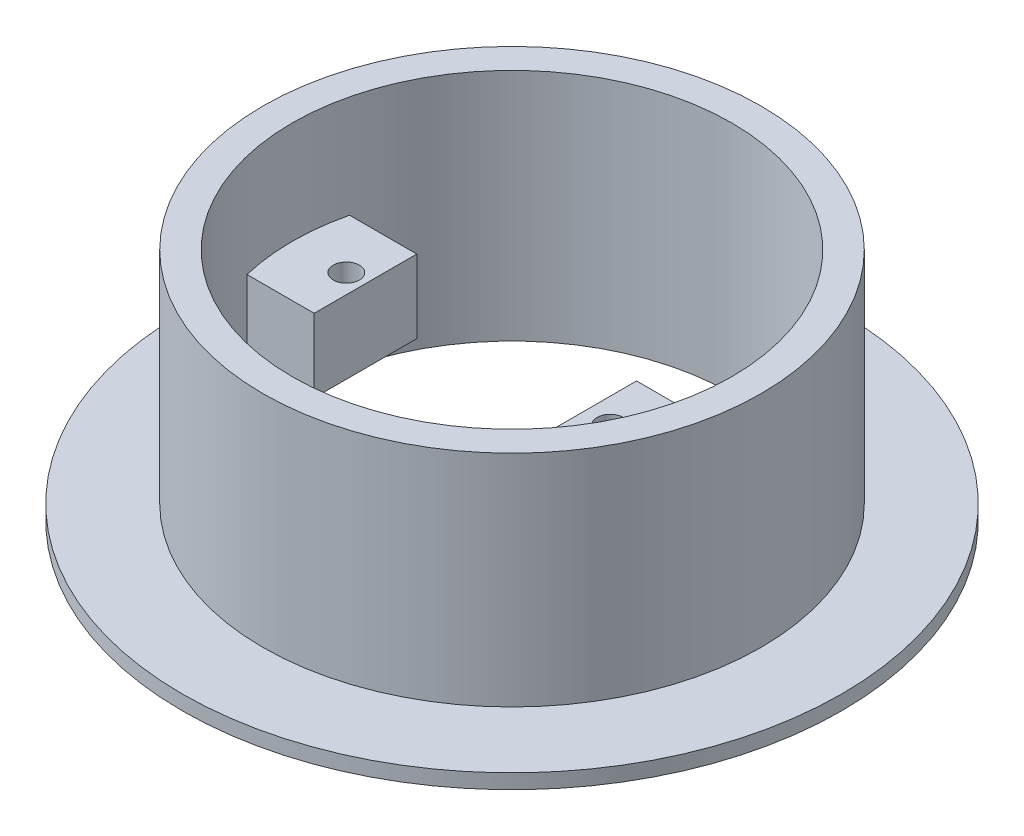
SolidWorks part; units mm, degrees
ref_plane "Front Plane" through (0, 0, 0) normal (0, 0, 1) x (1, 0, 0)
ref_plane "Top Plane" through (0, 0, 0) normal (0, 1, 0) x (1, 0, 0)
ref_plane "Right Plane" through (0, 0, 0) normal (1, 0, 0) x (0, 0, -1)
sketch "Sketch1" plane through (0, 0, 0) normal (0, 1, 0) x (1, 0, 0)
  circle A0 centre (0, 0) radius 45
  circle A1 centre (0, 0) radius 30
  dimension "D1" = 90
  dimension "D2" = 60
extrude "Boss-Extrude1" add sketch "Sketch1" along normal blind 2 contours A0
sketch "Sketch2" plane through (0, 2, 0) normal (0, 1, 0) x (1, 0, 0)
  circle A0 centre (0, 0) radius 30 construction
  circle A1 centre (0, 0) radius 30
  circle A2 centre (0, 0) radius 34
  dimension "D1" = 4
extrude "Boss-Extrude2" add sketch "Sketch2" along normal blind 30
ref_plane "Plane1" through (0, 12, 0) normal (0, 1, 0) x (1, 0, 0)
sketch "Sketch4" plane through (0, 0, 0) normal (0, 0, 1) x (1, 0, 0)
  line L0 (-45, 0) -> (45, 0) construction
  line L1 (10, 18) -> (17, 18)
  line L2 (10, 18) -> (10, 0)
  line L3 (10, 0) -> (17, 0)
  line L4 (17, 18) -> (17, 0)
  line L5 (34, 32) -> (-34, 32) construction
  line L6 (-30, 32) -> (-30, 2)
  line L7 (-20, 18) -> (-47, 18)
  line L8 (-20, 18) -> (-20, 8)
  line L9 (-20, 8) -> (-47, 8)
  line L10 (-47, 18) -> (-47, 8)
  line L11 (45, 2) -> (-45, 2) construction
  line L12 (-20, 8) -> (-30, -2)
  dimension "D1" = 10
  dimension "D2" = 7
  dimension "D3" = 14
  dimension "D4" = 30
  dimension "D5" = 27
  dimension "D6" = 10
  dimension "D7" = 45
  dimension "D8" = 14
extrude "Boss-Extrude4" add sketch "Sketch4" along normal mid plane 14 contours L9 L8 L7 L6 | L12 L9 L6 | L1 L4 L3 L2
sketch "Sketch5" plane through (0, 0, 0.8324) normal (0, -1, 0) x (1, 0, 0)
  line L0 (9.016, 9.8529) -> (26.6591, 12.9259)
  line L1 (9.016, -12.3037) -> (26.1127, -15.6015)
  line L2 (9.016, 9.8529) -> (9.016, -12.3037)
  circle A0 centre (0, -0.8324) radius 30 construction
  arc A1 (26.1127, -15.6015) -> (26.6591, 12.9259) centre (-0.5461, -0.822) ccw
extrude "Boss-Extrude5" add sketch "Sketch5" against normal up to surface (2 mm away) contours L0 A1 L1 L2 up to face at (0, 2, 45)
sketch "Sketch7" plane through (0, 18, 0) normal (0, 1, 0) x (1, 0, 0)
  circle A0 centre (-22.6116, 0) radius 1.775
  circle A1 centre (13.3884, 0) radius 1.775
  dimension "D1" = 36
  dimension "D2" = 3.55
extrude "Cut-Extrude1" cut sketch "Sketch7" against normal blind 8
